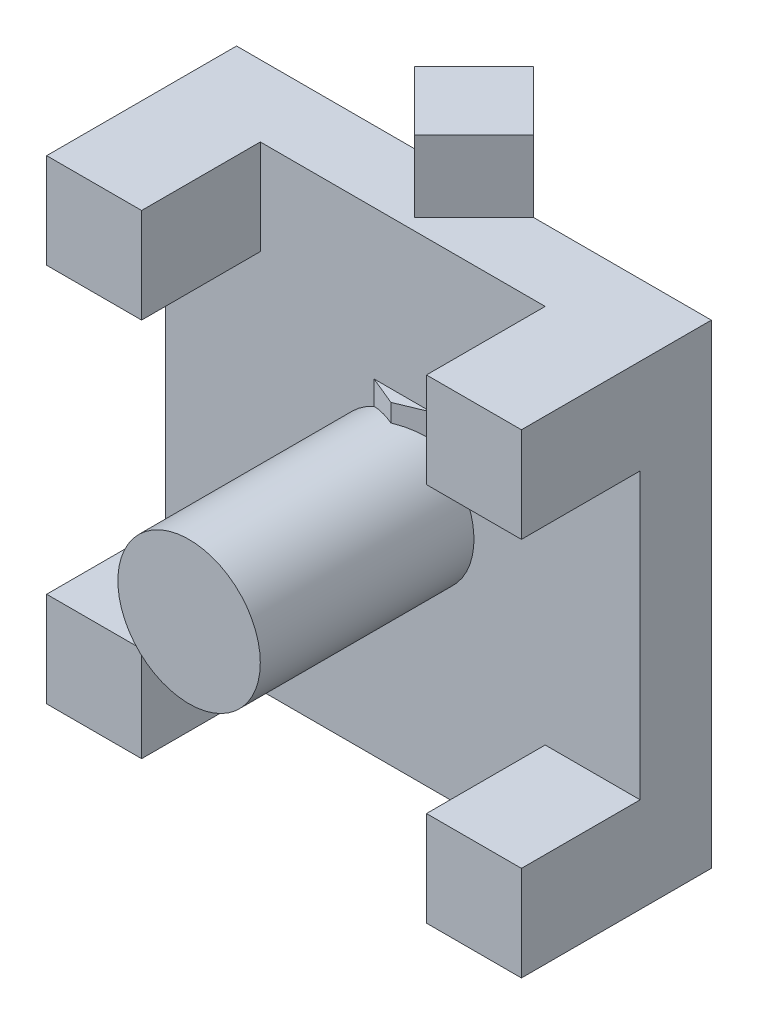
SolidWorks part; units mm, degrees
ref_plane "前视基准面" through (0, 0, 0) normal (0, 0, 1) x (1, 0, 0)
ref_plane "上视基准面" through (0, 0, 0) normal (0, 1, 0) x (1, 0, 0)
ref_plane "右视基准面" through (0, 0, 0) normal (1, 0, 0) x (0, 0, -1)
other "Configuration Table"
sketch "草图1" plane through (0, 0, 0) normal (0, 0, 1) x (1, 0, 0)
  line L1 (-1000, -1000) -> (1000, -1000)
  line L2 (-1000, -1000) -> (-1000, 1000)
  line L3 (-1000, 1000) -> (1000, 1000)
  line L4 (1000, -1000) -> (1000, 1000)
  line L5 (-1000, -1000) -> (1000, 1000) construction
  line L6 (-1000, 1000) -> (1000, -1000) construction
  point P0 (0, 0)
extrude "凸台-拉伸1" add sketch "草图1" along normal blind 300
sketch "草图2" plane through (0, 0, 0) normal (0, 0, 1) x (1, 0, 0)
  line L1 (-1000, -1000) -> (-600, -1000)
  line L2 (-1000, -1000) -> (-1000, -600)
  line L3 (-1000, -600) -> (-600, -600)
  line L4 (-600, -1000) -> (-600, -600)
  line L5 (-1000, -1000) -> (-600, -600) construction
  line L6 (-1000, -600) -> (-600, -1000) construction
  point P0 (-800, -800)
extrude "凸台-拉伸2" add sketch "草图2" along normal blind 800
sketch "草图3" plane through (0, 0, 0) normal (0, 0, 1) x (1, 0, 0)
  line L0 (1000, -1000) -> (1000, 1000) construction
  line L1 (600, -1000) -> (1000, -1000)
  line L2 (600, -1000) -> (600, -600)
  line L3 (600, -600) -> (1000, -600)
  line L4 (1000, -1000) -> (1000, -600)
  line L5 (600, -1000) -> (1000, -600) construction
  line L6 (600, -600) -> (1000, -1000) construction
  point P0 (800, -800)
extrude "凸台-拉伸3" add sketch "草图3" along normal blind 800
sketch "草图4" plane through (0, 0, 0) normal (0, 0, 1) x (1, 0, 0)
  line L0 (1000, 1000) -> (-1000, 1000) construction
  line L1 (-1000, 600) -> (-600, 600)
  line L2 (-1000, 600) -> (-1000, 1000)
  line L3 (-1000, 1000) -> (-600, 1000)
  line L4 (-600, 600) -> (-600, 1000)
  line L5 (-1000, 600) -> (-600, 1000) construction
  line L6 (-1000, 1000) -> (-600, 600) construction
  point P0 (-800, 800)
extrude "凸台-拉伸4" add sketch "草图4" along normal blind 800
sketch "草图5" plane through (0, 0, 0) normal (0, 0, 1) x (1, 0, 0)
  line L1 (600, 600) -> (1000, 600)
  line L2 (600, 600) -> (600, 1000)
  line L3 (600, 1000) -> (1000, 1000)
  line L4 (1000, 600) -> (1000, 1000)
  line L5 (600, 600) -> (1000, 1000) construction
  line L6 (600, 1000) -> (1000, 600) construction
  point P0 (800, 800)
extrude "凸台-拉伸5" add sketch "草图5" along normal blind 800
sketch "草图6" plane through (0, 0, 0) normal (0, 0, 1) x (1, 0, 0)
  circle A0 centre (0, 0) radius 300
extrude "凸台-拉伸6" add sketch "草图6" along normal blind 1200
sketch "草图7" plane through (0, 0, 300) normal (0, 0, 1) x (1, 0, 0)
  line L1 (-200, -25) -> (200, -25)
  line L2 (-200, -25) -> (-200, 25)
  line L3 (-200, 25) -> (200, 25)
  line L4 (200, -25) -> (200, 25)
  line L5 (-200, -25) -> (200, 25) construction
  line L6 (-200, 25) -> (200, -25) construction
  point P0 (0, 0)
extrude "切除-拉伸1" cut sketch "草图7" against normal through all
sketch "草图8" plane through (0, -600, 0) normal (0, 1, 0) x (1, 0, 0)
  line L1 (250, 0) -> (0, 250)
  line L2 (0, 250) -> (-250, 0)
  line L3 (-250, 0) -> (0, -250)
  line L4 (0, -250) -> (250, 0)
  circle A0 centre (0, 0) radius 176.7767 construction
extrude "凸台-拉伸7" add sketch "草图8" along normal blind 300
sketch "草图9" plane through (0, -600, 0) normal (0, 1, 0) x (1, 0, 0)
  line L1 (250, 0) -> (0, 250)
  line L2 (0, 250) -> (-250, 0)
  line L3 (-250, 0) -> (0, -250)
  line L4 (0, -250) -> (250, 0)
  circle A0 centre (0, 0) radius 176.7767 construction
extrude "凸台-拉伸8" add sketch "草图9" along normal blind 300
sketch "草图10" plane through (0, 1000, 0) normal (0, 1, 0) x (1, 0, 0)
  line L1 (250, 0) -> (0, 250)
  line L2 (0, 250) -> (-250, 0)
  line L3 (-250, 0) -> (0, -250)
  line L4 (0, -250) -> (250, 0)
  circle A0 centre (0, 0) radius 176.7767 construction
extrude "凸台-拉伸9" add sketch "草图10" along normal blind 300
sketch "草图11" plane through (0, 1000, 0) normal (0, 1, 0) x (1, 0, 0)
  line L1 (250, 0) -> (0, 250)
  line L2 (0, 250) -> (-250, 0)
  line L3 (-250, 0) -> (0, -250)
  line L4 (0, -250) -> (250, 0)
  circle A0 centre (0, 0) radius 176.7767 construction
extrude "凸台-拉伸10" add sketch "草图11" along normal blind 300
sketch "草图12" plane through (0, -25, 0) normal (0, 1, 0) x (1, 0, 0)
  line L1 (350, 0) -> (247.4874, 247.4874)
  line L2 (247.4874, 247.4874) -> (0, 350)
  line L3 (0, 350) -> (-247.4874, 247.4874)
  line L4 (-247.4874, 247.4874) -> (-350, 0)
  line L5 (-350, 0) -> (-247.4874, -247.4874)
  line L6 (-247.4874, -247.4874) -> (0, -350)
  line L7 (0, -350) -> (247.4874, -247.4874)
  line L8 (247.4874, -247.4874) -> (350, 0)
  circle A0 centre (0, 0) radius 323.3578 construction
extrude "凸台-拉伸11" add sketch "草图12" along normal blind 400
